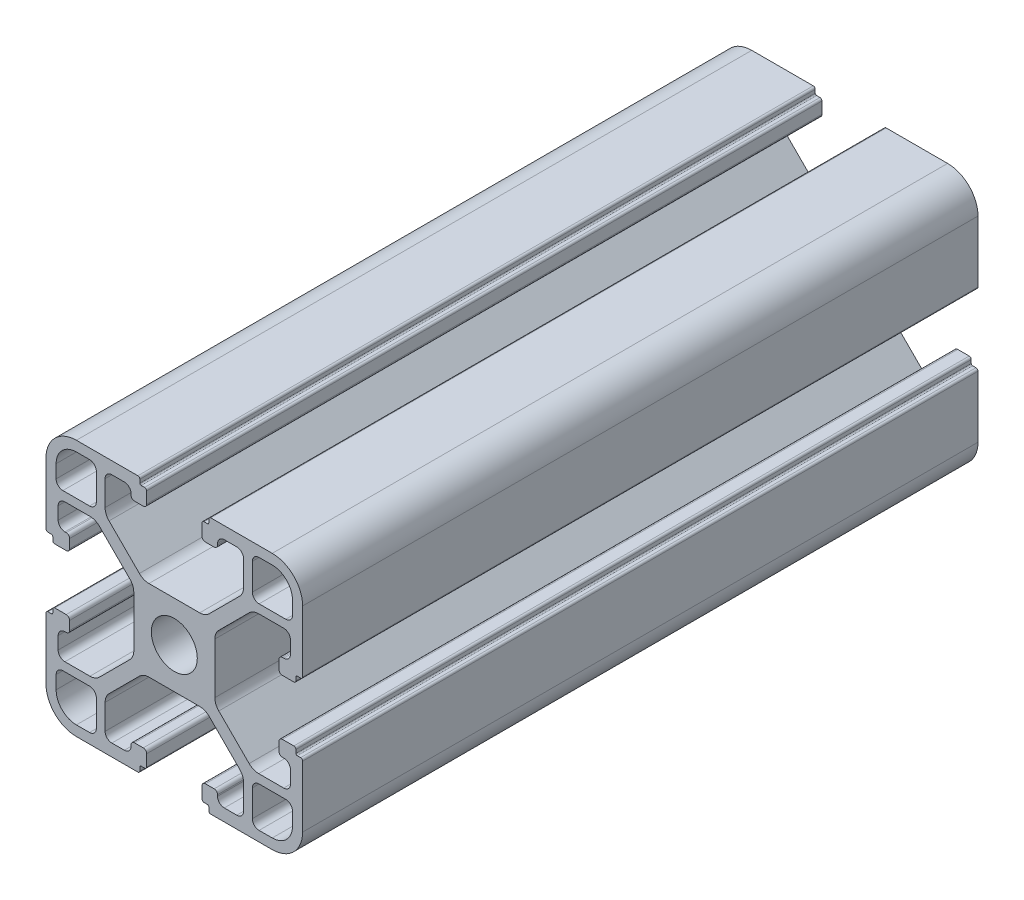
SolidWorks part; units mm, degrees
ref_plane "前视基准面" through (0, 0, 0) normal (0, 0, 1) x (1, 0, 0)
ref_plane "上视基准面" through (0, 0, 0) normal (0, 1, 0) x (1, 0, 0)
ref_plane "右视基准面" through (0, 0, 0) normal (1, 0, 0) x (0, 0, -1)
sketch "草图1" plane through (0, 0, 0) normal (0, 0, 1) x (1, 0, 0)
  line B0 (-5.1, -18.7) -> (-5.1, -18.2)
  line B1 (-4.9, -18) -> (-4.4, -18)
  line B2 (-4.1, -17.7) -> (-4.1, -16)
  line B3 (-4.6, -15.5) -> (-5.9, -15.5)
  line B4 (-6.4, -16) -> (-6.4, -16.2)
  line B5 (-7.4, -17.2) -> (-9.25, -17.2)
  line B6 (-10.25, -16.2) -> (-10.25, -12.4926)
  line B7 (-9.6642, -11.0784) -> (-5.1716, -6.5858)
  line B8 (-3.7574, -6) -> (3.7574, -6)
  line B9 (5.1716, -6.5858) -> (9.6642, -11.0784)
  line B10 (10.25, -12.4926) -> (10.25, -16.2)
  line B11 (9.25, -17.2) -> (7.4, -17.2)
  line B12 (6.4, -16.2) -> (6.4, -16)
  line B13 (5.9, -15.5) -> (4.6, -15.5)
  line B14 (4.1, -16) -> (4.1, -17.7)
  line B15 (4.4, -18) -> (4.9, -18)
  line B16 (5.1, -18.2) -> (5.1, -18.7)
  line B17 (5.4, -19) -> (14.5, -19)
  line B18 (19, -14.5) -> (19, -5.4)
  line B19 (18.7, -5.1) -> (18.2, -5.1)
  line B20 (18, -4.9) -> (18, -4.4)
  line B21 (17.7, -4.1) -> (16, -4.1)
  line B22 (15.5, -4.6) -> (15.5, -5.9)
  line B23 (16, -6.4) -> (16.2, -6.4)
  line B24 (17.2, -7.4) -> (17.2, -9.25)
  line B25 (16.2, -10.25) -> (12.4926, -10.25)
  line B26 (11.0784, -9.6642) -> (6.5858, -5.1716)
  line B27 (6, -3.7574) -> (6, 3.7574)
  line B28 (6.5858, 5.1716) -> (11.0784, 9.6642)
  line B29 (12.4926, 10.25) -> (16.2, 10.25)
  line B30 (17.2, 9.25) -> (17.2, 7.4)
  line B31 (16.2, 6.4) -> (16, 6.4)
  line B32 (15.5, 5.9) -> (15.5, 4.6)
  line B33 (16, 4.1) -> (17.7, 4.1)
  line B34 (18, 4.4) -> (18, 4.9)
  line B35 (18.2, 5.1) -> (18.7, 5.1)
  line B36 (19, 5.4) -> (19, 14.5)
  line B37 (14.5, 19) -> (5.4, 19)
  line B38 (5.1, 18.7) -> (5.1, 18.2)
  line B39 (4.9, 18) -> (4.4, 18)
  line B40 (4.1, 17.7) -> (4.1, 16)
  line B41 (4.6, 15.5) -> (5.9, 15.5)
  line B42 (6.4, 16) -> (6.4, 16.2)
  line B43 (7.4, 17.2) -> (9.25, 17.2)
  line B44 (10.25, 16.2) -> (10.25, 12.4926)
  line B45 (9.6642, 11.0784) -> (5.1716, 6.5858)
  line B46 (3.7574, 6) -> (-3.7574, 6)
  line B47 (-5.1716, 6.5858) -> (-9.6642, 11.0784)
  line B48 (-10.25, 12.4926) -> (-10.25, 16.2)
  line B49 (-9.25, 17.2) -> (-7.4, 17.2)
  line B50 (-6.4, 16.2) -> (-6.4, 16)
  line B51 (-5.9, 15.5) -> (-4.6, 15.5)
  line B52 (-4.1, 16) -> (-4.1, 17.7)
  line B53 (-4.4, 18) -> (-4.9, 18)
  line B54 (-5.1, 18.2) -> (-5.1, 18.7)
  line B55 (-5.4, 19) -> (-14.5, 19)
  line B56 (-19, 14.5) -> (-19, 5.4)
  line B57 (-18.7, 5.1) -> (-18.2, 5.1)
  line B58 (-18, 4.9) -> (-18, 4.4)
  line B59 (-17.7, 4.1) -> (-16, 4.1)
  line B60 (-15.5, 4.6) -> (-15.5, 5.9)
  line B61 (-16, 6.4) -> (-16.2, 6.4)
  line B62 (-17.2, 7.4) -> (-17.2, 9.25)
  line B63 (-16.2, 10.25) -> (-12.4926, 10.25)
  line B64 (-11.0784, 9.6642) -> (-6.5858, 5.1716)
  line B65 (-6, 3.7574) -> (-6, -3.7574)
  line B66 (-6.5858, -5.1716) -> (-11.0784, -9.6642)
  line B67 (-12.4926, -10.25) -> (-16.2, -10.25)
  line B68 (-17.2, -9.25) -> (-17.2, -7.4)
  line B69 (-16.2, -6.4) -> (-16, -6.4)
  line B70 (-15.5, -5.9) -> (-15.5, -4.6)
  line B71 (-16, -4.1) -> (-17.7, -4.1)
  line B72 (-18, -4.4) -> (-18, -4.9)
  line B73 (-18.2, -5.1) -> (-18.7, -5.1)
  line B74 (-19, -5.4) -> (-19, -14.5)
  line B75 (-14.5, -19) -> (-5.4, -19)
  line B76 (-14.5, -17.5) -> (-12.55, -17.5)
  line B77 (-11.55, -16.5) -> (-11.55, -12.55)
  line B78 (-12.55, -11.55) -> (-16.5, -11.55)
  line B79 (-17.5, -12.55) -> (-17.5, -14.5)
  line B80 (-12.55, 17.5) -> (-14.5, 17.5)
  line B81 (-17.5, 14.5) -> (-17.5, 12.55)
  line B82 (-16.5, 11.55) -> (-12.55, 11.55)
  line B83 (-11.55, 12.55) -> (-11.55, 16.5)
  line B84 (12.55, 11.55) -> (16.5, 11.55)
  line B85 (17.5, 12.55) -> (17.5, 14.5)
  line B86 (14.5, 17.5) -> (12.55, 17.5)
  line B87 (11.55, 16.5) -> (11.55, 12.55)
  line B88 (12.55, -17.5) -> (14.5, -17.5)
  line B89 (17.5, -14.5) -> (17.5, -12.55)
  line B90 (16.5, -11.55) -> (12.55, -11.55)
  line B91 (11.55, -12.55) -> (11.55, -16.5)
  arc B92 (-4.9, -18) -> (-5.1, -18.2) centre (-4.9, -18.2) ccw
  arc B93 (-4.4, -18) -> (-4.1, -17.7) centre (-4.4, -17.7) ccw
  arc B94 (-4.1, -16) -> (-4.6, -15.5) centre (-4.6, -16) ccw
  arc B95 (-5.9, -15.5) -> (-6.4, -16) centre (-5.9, -16) ccw
  arc B96 (-7.4, -17.2) -> (-6.4, -16.2) centre (-7.4, -16.2) ccw
  arc B97 (-10.25, -16.2) -> (-9.25, -17.2) centre (-9.25, -16.2) ccw
  arc B98 (-9.6642, -11.0784) -> (-10.25, -12.4926) centre (-8.25, -12.4926) ccw
  arc B99 (-3.7574, -6) -> (-5.1716, -6.5858) centre (-3.7574, -8) ccw
  arc B100 (5.1716, -6.5858) -> (3.7574, -6) centre (3.7574, -8) ccw
  arc B101 (10.25, -12.4926) -> (9.6642, -11.0784) centre (8.25, -12.4926) ccw
  arc B102 (9.25, -17.2) -> (10.25, -16.2) centre (9.25, -16.2) ccw
  arc B103 (6.4, -16.2) -> (7.4, -17.2) centre (7.4, -16.2) ccw
  arc B104 (6.4, -16) -> (5.9, -15.5) centre (5.9, -16) ccw
  arc B105 (4.6, -15.5) -> (4.1, -16) centre (4.6, -16) ccw
  arc B106 (4.1, -17.7) -> (4.4, -18) centre (4.4, -17.7) ccw
  arc B107 (5.1, -18.2) -> (4.9, -18) centre (4.9, -18.2) ccw
  arc B108 (5.1, -18.7) -> (5.4, -19) centre (5.4, -18.7) ccw
  arc B109 (14.5, -19) -> (19, -14.5) centre (14.5, -14.5) ccw
  arc B110 (19, -5.4) -> (18.7, -5.1) centre (18.7, -5.4) ccw
  arc B111 (18, -4.9) -> (18.2, -5.1) centre (18.2, -4.9) ccw
  arc B112 (18, -4.4) -> (17.7, -4.1) centre (17.7, -4.4) ccw
  arc B113 (16, -4.1) -> (15.5, -4.6) centre (16, -4.6) ccw
  arc B114 (15.5, -5.9) -> (16, -6.4) centre (16, -5.9) ccw
  arc B115 (17.2, -7.4) -> (16.2, -6.4) centre (16.2, -7.4) ccw
  arc B116 (16.2, -10.25) -> (17.2, -9.25) centre (16.2, -9.25) ccw
  arc B117 (11.0784, -9.6642) -> (12.4926, -10.25) centre (12.4926, -8.25) ccw
  arc B118 (6, -3.7574) -> (6.5858, -5.1716) centre (8, -3.7574) ccw
  arc B119 (6.5858, 5.1716) -> (6, 3.7574) centre (8, 3.7574) ccw
  arc B120 (12.4926, 10.25) -> (11.0784, 9.6642) centre (12.4926, 8.25) ccw
  arc B121 (17.2, 9.25) -> (16.2, 10.25) centre (16.2, 9.25) ccw
  arc B122 (16.2, 6.4) -> (17.2, 7.4) centre (16.2, 7.4) ccw
  arc B123 (16, 6.4) -> (15.5, 5.9) centre (16, 5.9) ccw
  arc B124 (15.5, 4.6) -> (16, 4.1) centre (16, 4.6) ccw
  arc B125 (17.7, 4.1) -> (18, 4.4) centre (17.7, 4.4) ccw
  arc B126 (18.2, 5.1) -> (18, 4.9) centre (18.2, 4.9) ccw
  arc B127 (18.7, 5.1) -> (19, 5.4) centre (18.7, 5.4) ccw
  arc B128 (19, 14.5) -> (14.5, 19) centre (14.5, 14.5) ccw
  arc B129 (5.4, 19) -> (5.1, 18.7) centre (5.4, 18.7) ccw
  arc B130 (4.9, 18) -> (5.1, 18.2) centre (4.9, 18.2) ccw
  arc B131 (4.4, 18) -> (4.1, 17.7) centre (4.4, 17.7) ccw
  arc B132 (4.1, 16) -> (4.6, 15.5) centre (4.6, 16) ccw
  arc B133 (5.9, 15.5) -> (6.4, 16) centre (5.9, 16) ccw
  arc B134 (7.4, 17.2) -> (6.4, 16.2) centre (7.4, 16.2) ccw
  arc B135 (10.25, 16.2) -> (9.25, 17.2) centre (9.25, 16.2) ccw
  arc B136 (9.6642, 11.0784) -> (10.25, 12.4926) centre (8.25, 12.4926) ccw
  arc B137 (3.7574, 6) -> (5.1716, 6.5858) centre (3.7574, 8) ccw
  arc B138 (-5.1716, 6.5858) -> (-3.7574, 6) centre (-3.7574, 8) ccw
  arc B139 (-10.25, 12.4926) -> (-9.6642, 11.0784) centre (-8.25, 12.4926) ccw
  arc B140 (-9.25, 17.2) -> (-10.25, 16.2) centre (-9.25, 16.2) ccw
  arc B141 (-6.4, 16.2) -> (-7.4, 17.2) centre (-7.4, 16.2) ccw
  arc B142 (-6.4, 16) -> (-5.9, 15.5) centre (-5.9, 16) ccw
  arc B143 (-4.6, 15.5) -> (-4.1, 16) centre (-4.6, 16) ccw
  arc B144 (-4.1, 17.7) -> (-4.4, 18) centre (-4.4, 17.7) ccw
  arc B145 (-5.1, 18.2) -> (-4.9, 18) centre (-4.9, 18.2) ccw
  arc B146 (-5.1, 18.7) -> (-5.4, 19) centre (-5.4, 18.7) ccw
  arc B147 (-14.5, 19) -> (-19, 14.5) centre (-14.5, 14.5) ccw
  arc B148 (-19, 5.4) -> (-18.7, 5.1) centre (-18.7, 5.4) ccw
  arc B149 (-18, 4.9) -> (-18.2, 5.1) centre (-18.2, 4.9) ccw
  arc B150 (-18, 4.4) -> (-17.7, 4.1) centre (-17.7, 4.4) ccw
  arc B151 (-16, 4.1) -> (-15.5, 4.6) centre (-16, 4.6) ccw
  arc B152 (-15.5, 5.9) -> (-16, 6.4) centre (-16, 5.9) ccw
  arc B153 (-17.2, 7.4) -> (-16.2, 6.4) centre (-16.2, 7.4) ccw
  arc B154 (-16.2, 10.25) -> (-17.2, 9.25) centre (-16.2, 9.25) ccw
  arc B155 (-11.0784, 9.6642) -> (-12.4926, 10.25) centre (-12.4926, 8.25) ccw
  arc B156 (-6, 3.7574) -> (-6.5858, 5.1716) centre (-8, 3.7574) ccw
  arc B157 (-6.5858, -5.1716) -> (-6, -3.7574) centre (-8, -3.7574) ccw
  arc B158 (-12.4926, -10.25) -> (-11.0784, -9.6642) centre (-12.4926, -8.25) ccw
  arc B159 (-17.2, -9.25) -> (-16.2, -10.25) centre (-16.2, -9.25) ccw
  arc B160 (-16.2, -6.4) -> (-17.2, -7.4) centre (-16.2, -7.4) ccw
  arc B161 (-16, -6.4) -> (-15.5, -5.9) centre (-16, -5.9) ccw
  arc B162 (-15.5, -4.6) -> (-16, -4.1) centre (-16, -4.6) ccw
  arc B163 (-17.7, -4.1) -> (-18, -4.4) centre (-17.7, -4.4) ccw
  arc B164 (-18.2, -5.1) -> (-18, -4.9) centre (-18.2, -4.9) ccw
  arc B165 (-18.7, -5.1) -> (-19, -5.4) centre (-18.7, -5.4) ccw
  arc B166 (-19, -14.5) -> (-14.5, -19) centre (-14.5, -14.5) ccw
  arc B167 (-5.4, -19) -> (-5.1, -18.7) centre (-5.4, -18.7) ccw
  arc B168 (-12.55, -17.5) -> (-11.55, -16.5) centre (-12.55, -16.5) ccw
  arc B169 (-11.55, -12.55) -> (-12.55, -11.55) centre (-12.55, -12.55) ccw
  arc B170 (-16.5, -11.55) -> (-17.5, -12.55) centre (-16.5, -12.55) ccw
  arc B171 (-17.5, -14.5) -> (-14.5, -17.5) centre (-14.5, -14.5) ccw
  arc B172 (-14.5, 17.5) -> (-17.5, 14.5) centre (-14.5, 14.5) ccw
  arc B173 (-17.5, 12.55) -> (-16.5, 11.55) centre (-16.5, 12.55) ccw
  arc B174 (-12.55, 11.55) -> (-11.55, 12.55) centre (-12.55, 12.55) ccw
  arc B175 (-11.55, 16.5) -> (-12.55, 17.5) centre (-12.55, 16.5) ccw
  arc B176 (16.5, 11.55) -> (17.5, 12.55) centre (16.5, 12.55) ccw
  arc B177 (17.5, 14.5) -> (14.5, 17.5) centre (14.5, 14.5) ccw
  arc B178 (12.55, 17.5) -> (11.55, 16.5) centre (12.55, 16.5) ccw
  arc B179 (11.55, 12.55) -> (12.55, 11.55) centre (12.55, 12.55) ccw
  arc B180 (14.5, -17.5) -> (17.5, -14.5) centre (14.5, -14.5) ccw
  arc B181 (17.5, -12.55) -> (16.5, -11.55) centre (16.5, -12.55) ccw
  arc B182 (12.55, -11.55) -> (11.55, -12.55) centre (12.55, -12.55) ccw
  arc B183 (11.55, -16.5) -> (12.55, -17.5) centre (12.55, -16.5) ccw
  circle B184 centre (0, 0) radius 3.4
sketch_block_instance "A$C11422B74-1"
sketch_block "A$C11422B74"
extrude "凸台-拉伸1" add sketch "草图1" along normal blind 100
